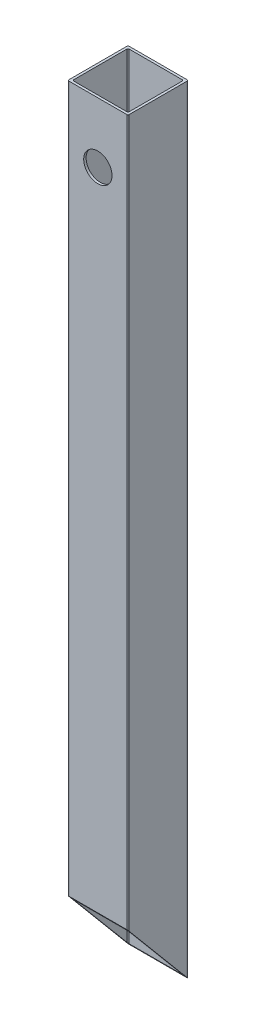
SolidWorks part; units mm, degrees
ref_plane "Plan de face" through (0, 0, 0) normal (0, 0, 1) x (1, 0, 0)
ref_plane "Plan de dessus" through (0, 0, 0) normal (0, 1, 0) x (1, 0, 0)
ref_plane "Plan de droite" through (0, 0, 0) normal (1, 0, 0) x (0, 0, -1)
sketch "Esquisse2" plane through (0, 0, 0) normal (0, 1, 0) x (1, 0, 0)
  line L0 (6, 96) -> (94, 96)
  line L1 (2, 0) -> (98, 0)
  line L2 (0, 2) -> (0, 98)
  line L3 (2, 100) -> (98, 100)
  line L4 (100, 2) -> (100, 98)
  line L5 (96, 6) -> (96, 94)
  line L6 (6, 4) -> (94, 4)
  line L7 (4, 6) -> (4, 94)
  line L8 (4, 4) -> (4, 96) construction
  line L9 (4, 96) -> (96, 96) construction
  line L10 (96, 4) -> (96, 96) construction
  line L11 (4, 4) -> (96, 4) construction
  line L12 (0, 0) -> (0, 100) construction
  line L13 (0, 0) -> (100, 0) construction
  line L14 (100, 0) -> (100, 100) construction
  line L15 (0, 100) -> (100, 100) construction
  arc A0 (4, 94) -> (6, 96) centre (6, 94) cw
  arc A1 (96, 6) -> (94, 4) centre (94, 6) cw
  arc A2 (6, 4) -> (4, 6) centre (6, 6) cw
  arc A3 (0, 2) -> (2, 0) centre (2, 2) ccw
  arc A4 (98, 0) -> (100, 2) centre (98, 2) ccw
  arc A5 (96, 94) -> (94, 96) centre (94, 94) ccw
  arc A6 (100, 98) -> (98, 100) centre (98, 98) ccw
  arc A7 (2, 100) -> (0, 98) centre (2, 98) ccw
  point P21 (0, 0)
  dimension "D4" = 2
  dimension "D1" = 100
  dimension "D2" = 100
  dimension "D3" = 4
extrude "Boss.-Extru.1" add sketch "Esquisse2" along normal blind 1500
sketch "Esquisse4" plane through (0, 0, 0) normal (-1, 0, 0) x (0, 0, 1)
  line L0 (-98, 1500) -> (-2, 1500) construction
  line L2 (-50, 200) -> (-50, 1500) construction
  line L4 (0, 150) -> (-100, 150) construction
  line L5 (-100, 1500) -> (-100, 0) construction
  line L6 (0, 1500) -> (0, 0) construction
  line L7 (-50, 200) -> (0, 200) construction
  line L8 (0, 200) -> (-206.801, -46.4558)
  line L13 (-206.801, -46.4558) -> (114.552, -46.4558)
  line L14 (114.552, -46.4558) -> (114.552, 200)
  line L15 (114.552, 200) -> (0, 200)
  circle A2 centre (-50, 200) radius 15 construction
  circle A3 centre (-50, 200) radius 50 construction
  point P4 (-50, 1274)
  point P15 (0, 200)
  point P22 (-50, 150)
  dimension "D6" = 30
  dimension "D1" = 1300
  dimension "D7" = 40
extrude "Enlèv. mat.-Extru.1" cut sketch "Esquisse4" against normal through all
sketch "Esquisse5" plane through (0, 0, -100) normal (0, 0, -1) x (-1, 0, 0)
  line L0 (-50, 1500) -> (-50, 1271) construction
  line L1 (-98, 1500) -> (-2, 1500) construction
  circle A0 centre (-50, 1271) radius 23.5
  dimension "D1" = 47
  dimension "D2" = 229
extrude "Enlèv. mat.-Extru.2" cut sketch "Esquisse5" against normal through all
sketch "Esquisse6" plane through (0, 0, -100) normal (0, 0, -1) x (-1, 0, 0)
  line L0 (0, 1500) -> (0, 197.6165) construction
  line L1 (-100, 1500) -> (0, 1500)
  line L2 (-100, 1500) -> (-100, 1371)
  line L3 (-100, 1371) -> (0, 1371)
  line L4 (0, 1500) -> (0, 1371)
  dimension "D1" = 129
extrude "Enlèv. mat.-Extru.3" cut sketch "Esquisse6" against normal through all
